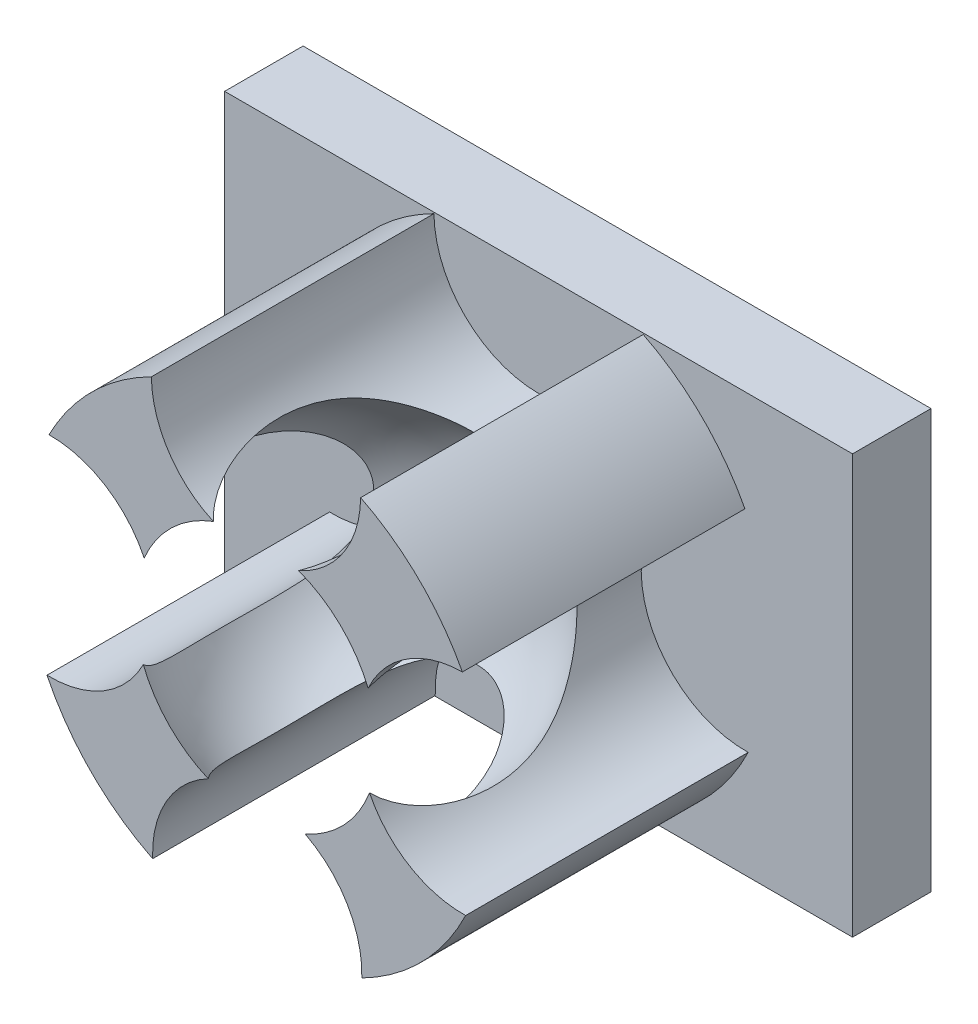
SolidWorks part; units mm, degrees
ref_plane "Ebene vorne" through (0, 0, 0) normal (0, 0, 1) x (1, 0, 0)
ref_plane "Ebene oben" through (0, 0, 0) normal (0, 1, 0) x (1, 0, 0)
ref_plane "Ebene rechts" through (0, 0, 0) normal (1, 0, 0) x (0, 0, -1)
sketch "Skizze1" plane through (0, 0, 0) normal (0, 0, 1) x (1, 0, 0)
  line L1 (12, 8) -> (-12, 8)
  line L2 (12, 8) -> (12, -8)
  line L3 (12, -8) -> (-12, -8)
  line L4 (-12, 8) -> (-12, -8)
  line L5 (12, 8) -> (-12, -8) construction
  line L6 (12, -8) -> (-12, 8) construction
  point P0 (0, 0)
  dimension "D1" = 24
  dimension "D2" = 16
extrude "Aufsatz-Linear austragen1" add sketch "Skizze1" along normal blind 3
sketch "Skizze2" plane through (0, 0, 3) normal (0, 0, 1) x (1, 0, 0)
  line L0 (0, 0) -> (0, 8) construction
  arc A0 (-3.9997, 7.9506) -> (-7.9113, 4.077) centre (0, 0) ccw
  arc A1 (-3.9997, 7.9506) -> (3.9997, 7.9506) centre (0, 8) ccw
  arc A2 (7.8872, 4.1233) -> (8.0119, -3.8755) centre (7.9228, 0.1235) ccw
  arc A3 (4.0442, -7.9281) -> (-3.9498, -7.9755) centre (0.0463, -7.7994) ccw
  arc A4 (-7.9896, -3.9212) -> (-7.9113, 4.077) centre (-7.8765, 0.0772) ccw
  arc A5 (7.8872, 4.1233) -> (3.9997, 7.9506) centre (0, 0) ccw
  arc A6 (4.0442, -7.9281) -> (8.0119, -3.8755) centre (0, 0) ccw
  arc A7 (-7.9896, -3.9212) -> (-3.9498, -7.9755) centre (0, 0) ccw
  point P14 (0.0231, 0.1003)
  dimension "D1" = 17.8
  dimension "D2" = 8
  dimension "D3" = 8
  dimension "D4" = 4
extrude "Aufsatz-Linear austragen2" add sketch "Skizze2" along normal blind 10.8
sketch "Skizze3" plane through (0, 0, 0) normal (0, 1, 0) x (1, 0, 0)
  line L0 (0, -4) -> (0, -10) construction
  line L1 (0, -10) -> (0, -16) construction
  line L2 (12, 0) -> (-12, 0) construction
  line L3 (0, -4) -> (0, -16)
  arc A0 (0, -16) -> (0, -4) centre (0, -10) ccw
  point P5 (0, -3.9614)
  dimension "D1" = 6
  dimension "D2" = 16
revolve "Schnitt-Rotation1" cut sketch "Skizze3" angle 360 about L3
